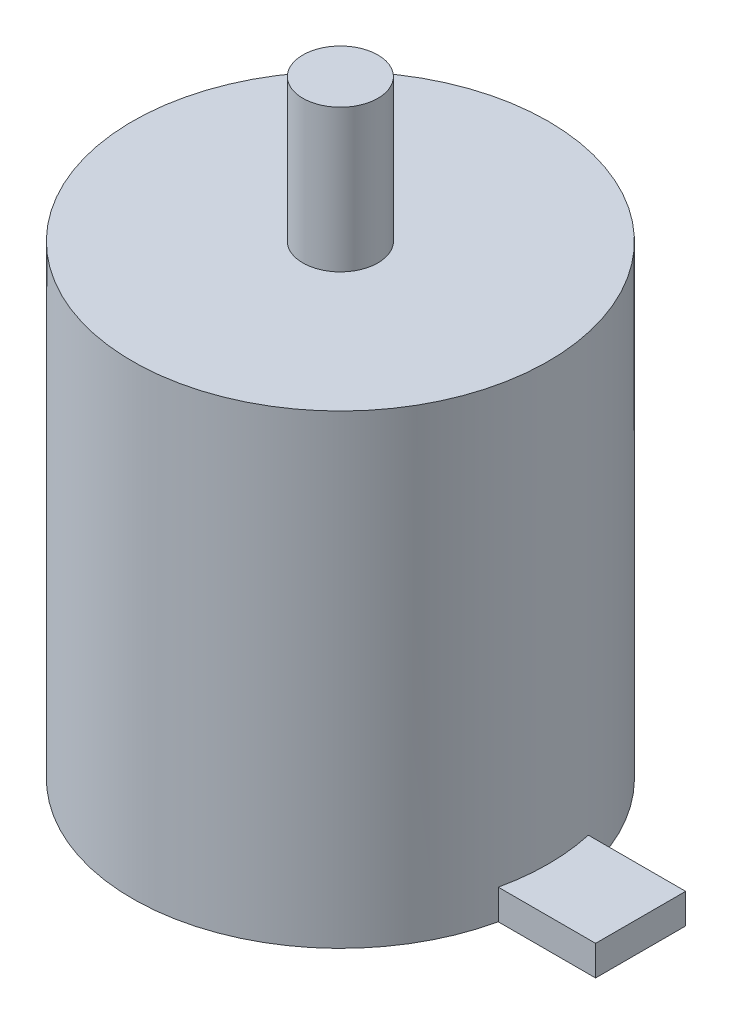
SolidWorks part; units mm, degrees
ref_plane "Спереди" through (0, 0, 0) normal (0, 0, 1) x (1, 0, 0)
ref_plane "Сверху" through (0, 0, 0) normal (0, 1, 0) x (1, 0, 0)
ref_plane "Справа" through (0, 0, 0) normal (1, 0, 0) x (0, 0, -1)
other "Configuration Table"
sketch "Эскиз2" plane through (0, 0, 0) normal (1, 0, 0) x (0, 0, -1)
  line L0 (0, 0) -> (0, 31)
  line L1 (1.5, 0) -> (13.85, 0)
  line L2 (2.5, 40.5) -> (2.5, 31)
  line L3 (0, 31) -> (0, 40.5)
  line L4 (0, 40.5) -> (2.5, 40.5)
  line L5 (2.5, 31) -> (13.85, 31)
  line L6 (13.85, 31) -> (13.85, 0)
  line L7 (0, 0) -> (0, -2)
  line L8 (0, -2) -> (1.5, -2)
  line L9 (1.5, -2) -> (1.5, 0)
revolve "Повернуть1" add sketch "Эскиз2" angle 360 about L0
sketch "Эскиз3" plane through (0, 0, 0) normal (0, -1, 0) x (1, 0, 0)
  line L0 (-13.85, 13.85) -> (13.85, -13.85) construction
  line L2 (-9.843, -9.843) -> (9.843, 9.843) construction
  circle A0 centre (5.6569, 5.6569) radius 1.25
  circle A1 centre (6.7175, -6.7175) radius 1.25
  circle A2 centre (-6.7175, 6.7175) radius 1.25
  circle A3 centre (-5.6569, -5.6569) radius 1.25
  point P12 (0, 0)
extrude "Вырез-Вытянуть1" cut sketch "Эскиз3" against normal blind 5
sketch "Эскиз4" plane through (0, 0, 0) normal (0, -1, 0) x (1, 0, 0)
  line L0 (13.85, -3) -> (12.85, -3)
  line L4 (12.85, -3) -> (20, -3)
  line L5 (12.85, -3) -> (12.85, 3)
  line L6 (12.85, 3) -> (20, 3)
  line L7 (20, -3) -> (20, 3)
  circle M7 centre (0, 0) radius 13.85
extrude "Бобышка-Вытянуть1" add sketch "Эскиз4" against normal blind 2 contours L4 L7 L6 L0 M7
